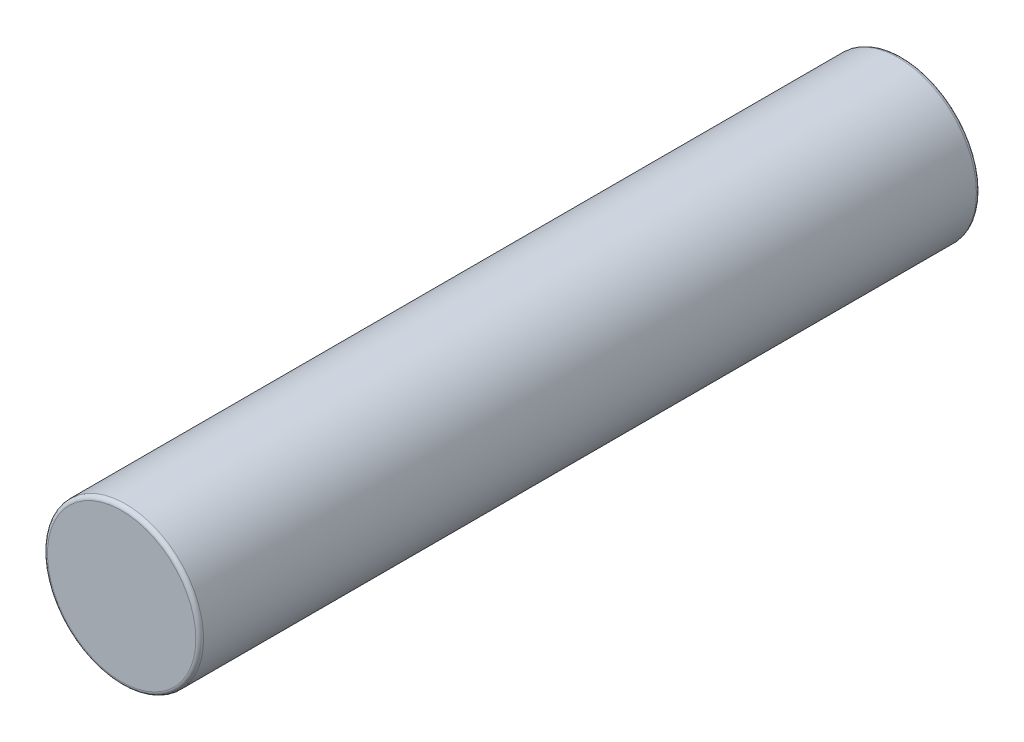
SolidWorks part; units mm, degrees
ref_plane "Front Plane" through (0, 0, 0) normal (0, 0, 1) x (1, 0, 0)
ref_plane "Top Plane" through (0, 0, 0) normal (0, 1, 0) x (1, 0, 0)
ref_plane "Right Plane" through (0, 0, 0) normal (1, 0, 0) x (0, 0, -1)
sketch "Sketch1" plane through (0, 0, 0) normal (0, 0, 1) x (1, 0, 0)
  circle A0 centre (0, 0) radius 20
  dimension "D1" = 40
extrude "Boss-Extrude1" add sketch "Sketch1" along normal blind 200
fillet "Fillet1" radius 1 2 edges at (20, 0, 0) (20, 0, 200)
